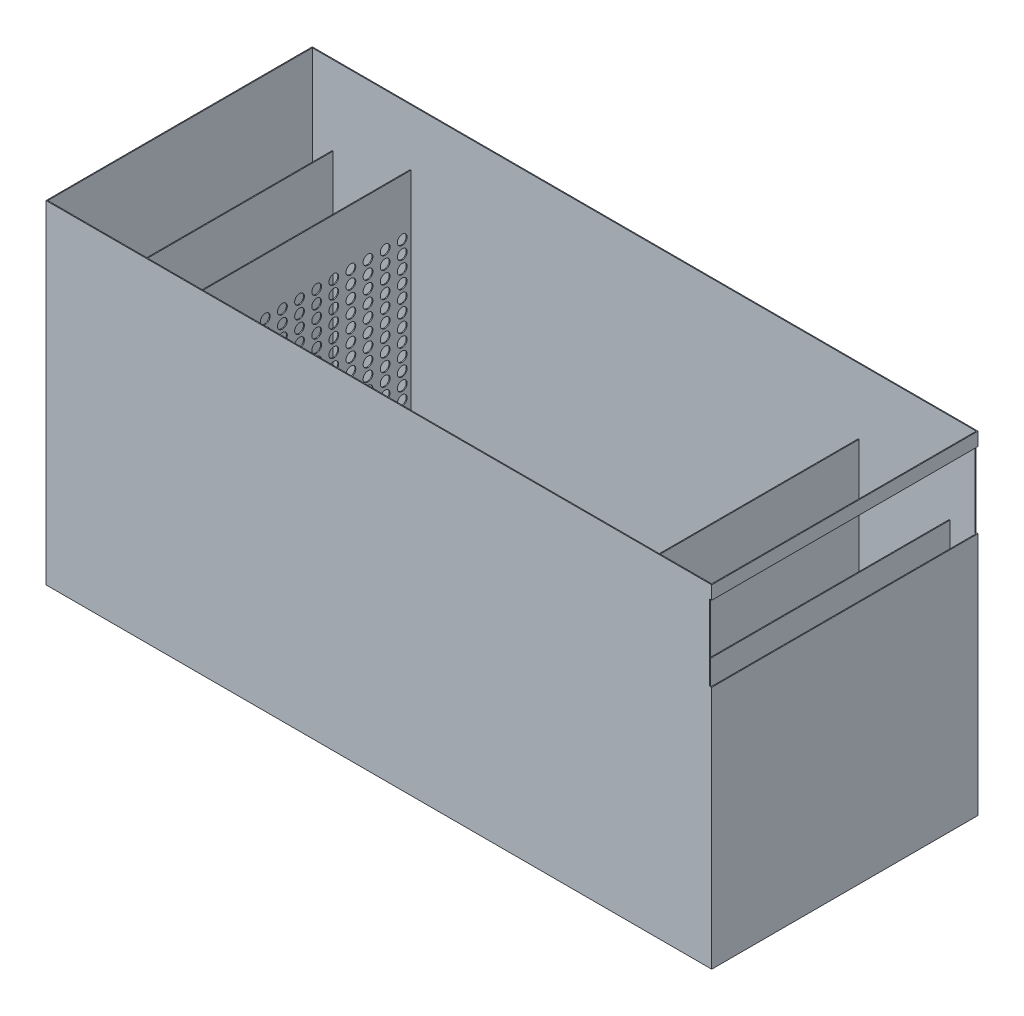
SolidWorks part; units mm, degrees
ref_plane "Спереди" through (0, 0, 0) normal (0, 0, 1) x (1, 0, 0)
ref_plane "Сверху" through (0, 0, 0) normal (0, 1, 0) x (1, 0, 0)
ref_plane "Справа" through (0, 0, 0) normal (1, 0, 0) x (0, 0, -1)
sketch "MASTER_FOOTPRINT" plane through (0, 0, 0) normal (0, 1, 0) x (1, 0, 0)
  line L1 (0, 0) -> (1500, 0)
  line L2 (0, 0) -> (0, 600)
  line L3 (0, 600) -> (1500, 600)
  line L4 (1500, 0) -> (1500, 600)
  dimension "D1" = 1500
  dimension "D2" = 600
extrude "BATH_BASE_PLATE" add sketch "MASTER_FOOTPRINT" along normal blind 750
shell "BATH_SHELL_2MM" thickness 2
sketch "Эскиз1" plane through (0, 0, 0) normal (1, 0, 0) x (0, 0, -1)
  circle A0 centre (300, 420) radius 50
extrude "INLET_D100_OPENING" cut sketch "Эскиз1" along normal blind 10
sketch "Эскиз2" plane through (0, 0, 0) normal (1, 0, 0) x (0, 0, -1)
  line L1 (80, 220) -> (520, 220)
  line L2 (80, 220) -> (80, 650)
  line L3 (80, 650) -> (520, 650)
  line L4 (520, 220) -> (520, 650)
extrude "INLET_IMPACT_BAFFLE" add sketch "Эскиз2" along normal blind 2 from offset 125 separate body
sketch "Эскиз3" plane through (0, 0, 0) normal (1, 0, 0) x (0, 0, -1)
  line L1 (30, 2) -> (570, 2)
  line L2 (30, 2) -> (30, 650)
  line L3 (30, 650) -> (570, 650)
  line L4 (570, 2) -> (570, 650)
  circle A0 centre (49.2857, 125) radius 11
  circle A1 centre (49.2857, 153.5) radius 11
  circle A2 centre (49.2857, 182) radius 11
  circle A3 centre (49.2857, 210.5) radius 11
  circle A4 centre (49.2857, 239) radius 11
  circle A5 centre (49.2857, 267.5) radius 11
  circle A6 centre (49.2857, 296) radius 11
  circle A7 centre (49.2857, 324.5) radius 11
  circle A8 centre (49.2857, 353) radius 11
  circle A9 centre (49.2857, 381.5) radius 11
  circle A10 centre (49.2857, 410) radius 11
  circle A11 centre (49.2857, 438.5) radius 11
  circle A12 centre (49.2857, 467) radius 11
  circle A13 centre (49.2857, 495.5) radius 11
  circle A14 centre (49.2857, 524) radius 11
  circle A15 centre (87.8571, 125) radius 11
  circle A16 centre (87.8571, 153.5) radius 11
  circle A17 centre (87.8571, 182) radius 11
  circle A18 centre (87.8571, 210.5) radius 11
  circle A19 centre (87.8571, 239) radius 11
  circle A20 centre (87.8571, 267.5) radius 11
  circle A21 centre (87.8571, 296) radius 11
  circle A22 centre (87.8571, 324.5) radius 11
  circle A23 centre (87.8571, 353) radius 11
  circle A24 centre (87.8571, 381.5) radius 11
  circle A25 centre (87.8571, 410) radius 11
  circle A26 centre (87.8571, 438.5) radius 11
  circle A27 centre (87.8571, 467) radius 11
  circle A28 centre (87.8571, 495.5) radius 11
  circle A29 centre (87.8571, 524) radius 11
  circle A30 centre (126.4286, 125) radius 11
  circle A31 centre (126.4286, 153.5) radius 11
  circle A32 centre (126.4286, 182) radius 11
  circle A33 centre (126.4286, 210.5) radius 11
  circle A34 centre (126.4286, 239) radius 11
  circle A35 centre (126.4286, 267.5) radius 11
  circle A36 centre (126.4286, 296) radius 11
  circle A37 centre (126.4286, 324.5) radius 11
  circle A38 centre (126.4286, 353) radius 11
  circle A39 centre (126.4286, 381.5) radius 11
  circle A40 centre (126.4286, 410) radius 11
  circle A41 centre (126.4286, 438.5) radius 11
  circle A42 centre (126.4286, 467) radius 11
  circle A43 centre (126.4286, 495.5) radius 11
  circle A44 centre (126.4286, 524) radius 11
  circle A45 centre (165, 125) radius 11
  circle A46 centre (165, 153.5) radius 11
  circle A47 centre (165, 182) radius 11
  circle A48 centre (165, 210.5) radius 11
  circle A49 centre (165, 239) radius 11
  circle A50 centre (165, 267.5) radius 11
  circle A51 centre (165, 296) radius 11
  circle A52 centre (165, 324.5) radius 11
  circle A53 centre (165, 353) radius 11
  circle A54 centre (165, 381.5) radius 11
  circle A55 centre (165, 410) radius 11
  circle A56 centre (165, 438.5) radius 11
  circle A57 centre (165, 467) radius 11
  circle A58 centre (165, 495.5) radius 11
  circle A59 centre (165, 524) radius 11
  circle A60 centre (203.5714, 125) radius 11
  circle A61 centre (203.5714, 153.5) radius 11
  circle A62 centre (203.5714, 182) radius 11
  circle A63 centre (203.5714, 210.5) radius 11
  circle A64 centre (203.5714, 239) radius 11
  circle A65 centre (203.5714, 267.5) radius 11
  circle A66 centre (203.5714, 296) radius 11
  circle A67 centre (203.5714, 324.5) radius 11
  circle A68 centre (203.5714, 353) radius 11
  circle A69 centre (203.5714, 381.5) radius 11
  circle A70 centre (203.5714, 410) radius 11
  circle A71 centre (203.5714, 438.5) radius 11
  circle A72 centre (203.5714, 467) radius 11
  circle A73 centre (203.5714, 495.5) radius 11
  circle A74 centre (203.5714, 524) radius 11
  circle A75 centre (242.1429, 125) radius 11
  circle A76 centre (242.1429, 153.5) radius 11
  circle A77 centre (242.1429, 182) radius 11
  circle A78 centre (242.1429, 210.5) radius 11
  circle A79 centre (242.1429, 239) radius 11
  circle A80 centre (242.1429, 267.5) radius 11
  circle A81 centre (242.1429, 296) radius 11
  circle A82 centre (242.1429, 324.5) radius 11
  circle A83 centre (242.1429, 353) radius 11
  circle A84 centre (242.1429, 381.5) radius 11
  circle A85 centre (242.1429, 410) radius 11
  circle A86 centre (242.1429, 438.5) radius 11
  circle A87 centre (242.1429, 467) radius 11
  circle A88 centre (242.1429, 495.5) radius 11
  circle A89 centre (242.1429, 524) radius 11
  circle A90 centre (280.7143, 125) radius 11
  circle A91 centre (280.7143, 153.5) radius 11
  circle A92 centre (280.7143, 182) radius 11
  circle A93 centre (280.7143, 210.5) radius 11
  circle A94 centre (280.7143, 239) radius 11
  circle A95 centre (280.7143, 267.5) radius 11
  circle A96 centre (280.7143, 296) radius 11
  circle A97 centre (280.7143, 324.5) radius 11
  circle A98 centre (280.7143, 353) radius 11
  circle A99 centre (280.7143, 381.5) radius 11
  circle A100 centre (280.7143, 410) radius 11
  circle A101 centre (280.7143, 438.5) radius 11
  circle A102 centre (280.7143, 467) radius 11
  circle A103 centre (280.7143, 495.5) radius 11
  circle A104 centre (280.7143, 524) radius 11
  circle A105 centre (319.2857, 125) radius 11
  circle A106 centre (319.2857, 153.5) radius 11
  circle A107 centre (319.2857, 182) radius 11
  circle A108 centre (319.2857, 210.5) radius 11
  circle A109 centre (319.2857, 239) radius 11
  circle A110 centre (319.2857, 267.5) radius 11
  circle A111 centre (319.2857, 296) radius 11
  circle A112 centre (319.2857, 324.5) radius 11
  circle A113 centre (319.2857, 353) radius 11
  circle A114 centre (319.2857, 381.5) radius 11
  circle A115 centre (319.2857, 410) radius 11
  circle A116 centre (319.2857, 438.5) radius 11
  circle A117 centre (319.2857, 467) radius 11
  circle A118 centre (319.2857, 495.5) radius 11
  circle A119 centre (319.2857, 524) radius 11
  circle A120 centre (357.8571, 125) radius 11
  circle A121 centre (357.8571, 153.5) radius 11
  circle A122 centre (357.8571, 182) radius 11
  circle A123 centre (357.8571, 210.5) radius 11
  circle A124 centre (357.8571, 239) radius 11
  circle A125 centre (357.8571, 267.5) radius 11
  circle A126 centre (357.8571, 296) radius 11
  circle A127 centre (357.8571, 324.5) radius 11
  circle A128 centre (357.8571, 353) radius 11
  circle A129 centre (357.8571, 381.5) radius 11
  circle A130 centre (357.8571, 410) radius 11
  circle A131 centre (357.8571, 438.5) radius 11
  circle A132 centre (357.8571, 467) radius 11
  circle A133 centre (357.8571, 495.5) radius 11
  circle A134 centre (357.8571, 524) radius 11
  circle A135 centre (396.4286, 125) radius 11
  circle A136 centre (396.4286, 153.5) radius 11
  circle A137 centre (396.4286, 182) radius 11
  circle A138 centre (396.4286, 210.5) radius 11
  circle A139 centre (396.4286, 239) radius 11
  circle A140 centre (396.4286, 267.5) radius 11
  circle A141 centre (396.4286, 296) radius 11
  circle A142 centre (396.4286, 324.5) radius 11
  circle A143 centre (396.4286, 353) radius 11
  circle A144 centre (396.4286, 381.5) radius 11
  circle A145 centre (396.4286, 410) radius 11
  circle A146 centre (396.4286, 438.5) radius 11
  circle A147 centre (396.4286, 467) radius 11
  circle A148 centre (396.4286, 495.5) radius 11
  circle A149 centre (396.4286, 524) radius 11
  circle A150 centre (435, 125) radius 11
  circle A151 centre (435, 153.5) radius 11
  circle A152 centre (435, 182) radius 11
  circle A153 centre (435, 210.5) radius 11
  circle A154 centre (435, 239) radius 11
  circle A155 centre (435, 267.5) radius 11
  circle A156 centre (435, 296) radius 11
  circle A157 centre (435, 324.5) radius 11
  circle A158 centre (435, 353) radius 11
  circle A159 centre (435, 381.5) radius 11
  circle A160 centre (435, 410) radius 11
  circle A161 centre (435, 438.5) radius 11
  circle A162 centre (435, 467) radius 11
  circle A163 centre (435, 495.5) radius 11
  circle A164 centre (435, 524) radius 11
  circle A165 centre (473.5714, 125) radius 11
  circle A166 centre (473.5714, 153.5) radius 11
  circle A167 centre (473.5714, 182) radius 11
  circle A168 centre (473.5714, 210.5) radius 11
  circle A169 centre (473.5714, 239) radius 11
  circle A170 centre (473.5714, 267.5) radius 11
  circle A171 centre (473.5714, 296) radius 11
  circle A172 centre (473.5714, 324.5) radius 11
  circle A173 centre (473.5714, 353) radius 11
  circle A174 centre (473.5714, 381.5) radius 11
  circle A175 centre (473.5714, 410) radius 11
  circle A176 centre (473.5714, 438.5) radius 11
  circle A177 centre (473.5714, 467) radius 11
  circle A178 centre (473.5714, 495.5) radius 11
  circle A179 centre (473.5714, 524) radius 11
  circle A180 centre (512.1429, 125) radius 11
  circle A181 centre (512.1429, 153.5) radius 11
  circle A182 centre (512.1429, 182) radius 11
  circle A183 centre (512.1429, 210.5) radius 11
  circle A184 centre (512.1429, 239) radius 11
  circle A185 centre (512.1429, 267.5) radius 11
  circle A186 centre (512.1429, 296) radius 11
  circle A187 centre (512.1429, 324.5) radius 11
  circle A188 centre (512.1429, 353) radius 11
  circle A189 centre (512.1429, 381.5) radius 11
  circle A190 centre (512.1429, 410) radius 11
  circle A191 centre (512.1429, 438.5) radius 11
  circle A192 centre (512.1429, 467) radius 11
  circle A193 centre (512.1429, 495.5) radius 11
  circle A194 centre (512.1429, 524) radius 11
  circle A195 centre (550.7143, 125) radius 11
  circle A196 centre (550.7143, 153.5) radius 11
  circle A197 centre (550.7143, 182) radius 11
  circle A198 centre (550.7143, 210.5) radius 11
  circle A199 centre (550.7143, 239) radius 11
  circle A200 centre (550.7143, 267.5) radius 11
  circle A201 centre (550.7143, 296) radius 11
  circle A202 centre (550.7143, 324.5) radius 11
  circle A203 centre (550.7143, 353) radius 11
  circle A204 centre (550.7143, 381.5) radius 11
  circle A205 centre (550.7143, 410) radius 11
  circle A206 centre (550.7143, 438.5) radius 11
  circle A207 centre (550.7143, 467) radius 11
  circle A208 centre (550.7143, 495.5) radius 11
  circle A209 centre (550.7143, 524) radius 11
extrude "DISTRIBUTOR_D22" add sketch "Эскиз3" along normal blind 2 from offset 250 separate body
sketch "Эскиз4" plane through (0, 0, 0) normal (1, 0, 0) x (0, 0, -1)
  line L1 (50, 320) -> (550, 320)
  line L2 (50, 320) -> (50, 650)
  line L3 (50, 650) -> (550, 650)
  line L4 (550, 320) -> (550, 650)
extrude "OUTLET_SUBMERGED_BAFFLE" add sketch "Эскиз4" along normal blind 2 from offset 1280 separate body
sketch "Эскиз5" plane through (0, 0, 0) normal (1, 0, 0) x (0, 0, -1)
  line L1 (5, 2) -> (595, 2)
  line L2 (5, 2) -> (5, 550)
  line L3 (5, 550) -> (595, 550)
  line L4 (595, 2) -> (595, 550)
extrude "OVERFLOW_WEIR_Z550" add sketch "Эскиз5" along normal blind 2 from offset 1440 separate body
sketch "Эскиз6" plane through (0, 0, 0) normal (1, 0, 0) x (0, 0, -1)
  line L0 (0, 750) -> (0, 0) construction
  line L1 (0, 550) -> (600, 550)
  line L2 (0, 550) -> (0, 720)
  line L3 (0, 720) -> (600, 720)
  line L4 (600, 550) -> (600, 720)
  line L5 (600, 750) -> (600, 0) construction
extrude "OUTLET_WEIR_SLOT_W600" cut sketch "Эскиз6" along normal blind 10 from offset 1495
sketch "Эскиз7" plane through (0, 0, 0) normal (1, 0, 0) x (0, 0, -1)
  line L0 (2, -1) -> (2, 120)
  line L1 (2, 120) -> (230, -1)
  line L2 (230, -1) -> (2, -1)
  line L3 (598, -1) -> (598, 120)
  line L4 (598, 120) -> (370, -1)
  line L5 (370, -1) -> (598, -1)
extrude "SLOPED_SEDIMENT_FLOOR" add sketch "Эскиз7" along normal blind 975 from offset 275
sketch3d "SCREW_AXIS_30DEG_REFERENCE"
  line L0 (400, 70, -300) -> (1600, 762.8203, -300)
equation "\"AI_Q_Peak\"= 0.006"
equation "\"AI_B_Bath\" = 600"
equation "\"AI_L_Settle\" = 1050"
equation "\"AI_L_Inlet\"= 250"
equation "\"AI_L_Outlet\"= 200"
equation "\"AI_L_Bath\" = 1500"
equation "\"AI_H_Water\"= 550"
equation "\"AI_H_Freeboard\"= 200"
equation "\"AI_H_Bath\"= 750"
equation "\"AI_Shell_Thickness\"= 2"
equation "\"AI_Inlet_DN\"= 100"
equation "\"AI_Weir_Width\"= 600"
equation "\"AI_Inlet_Baffle_Offset\"= 125"
equation "\"AI_Distributor_Open_Area\"= 0.28"
equation "\"AI_Distributor_Hole_Dia\"= 22"
equation "\"AI_Distributor_Blind_Zone\"= 110"
equation "\"AI_Outlet_Baffle_Depth\"= 250"
equation "\"AI_Screw_Diameter\"= 100"
equation "\"AI_Screw_Pitch\"= 100"
equation "\"AI_Screw_Angle\"= 30"
equation "\"AI_Screw_Rpm\"= 15"
equation "\"AI_Screw_Clearance\"= 5"
equation "\"AI_Liner_Thickness\"= 5"
equation "\"AI_Discharge_Height\"= 650"
equation "\"AI_Frame_Height\"= 500"
equation "\"D1@MASTER_FOOTPRINT\" = \"AI_L_Bath\""
equation "\"D2@MASTER_FOOTPRINT\" = \"AI_B_Bath\""
equation "\"D1@BATH_BASE_PLATE\" = \"AI_H_Bath\""
